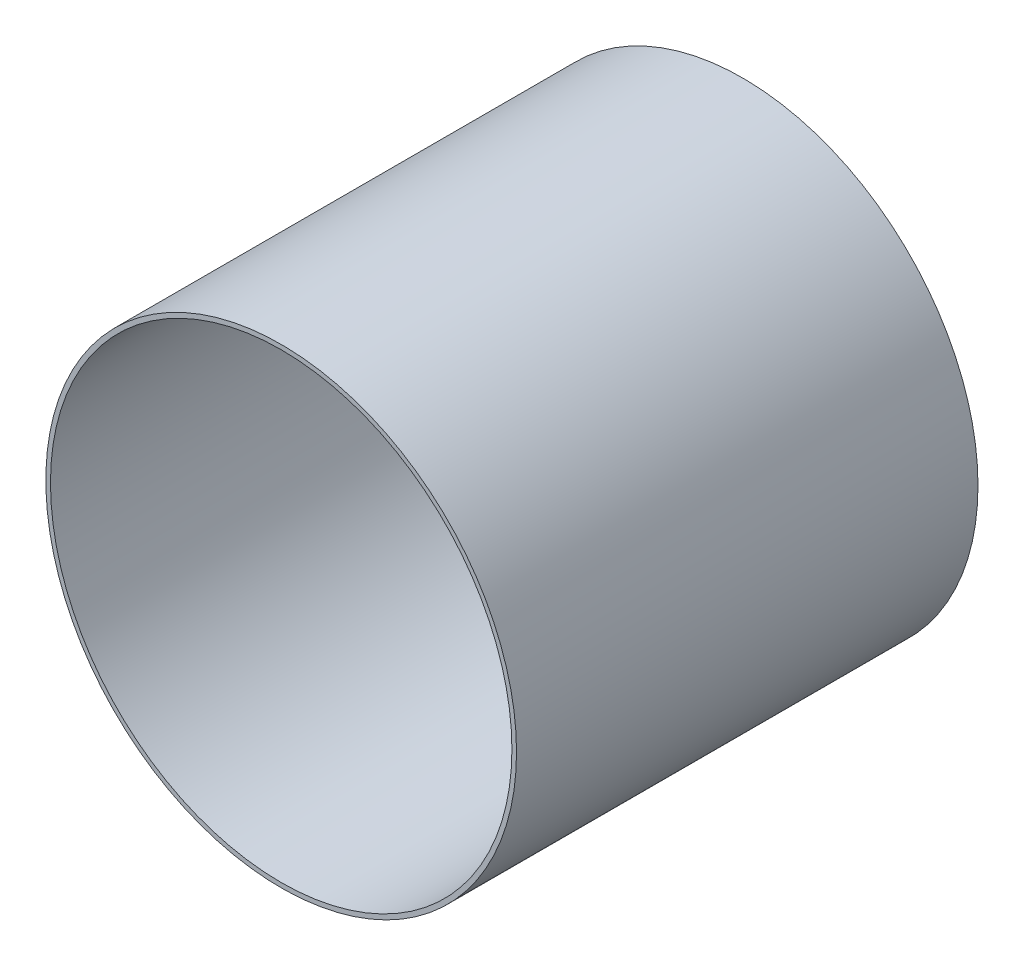
SolidWorks part; units mm, degrees
ref_plane "Спереди" through (0, 0, 0) normal (0, 0, 1) x (1, 0, 0)
ref_plane "Сверху" through (0, 0, 0) normal (0, 1, 0) x (1, 0, 0)
ref_plane "Справа" through (0, 0, 0) normal (1, 0, 0) x (0, 0, -1)
sketch "Эскиз1" plane through (0, 0, 0) normal (0, 0, 1) x (1, 0, 0)
  circle A0 centre (0, 0) radius 100
  dimension "D1" = 200
extrude "Вытянуть-Тонкостенный1" add sketch "Эскиз1" along normal blind 200 thin
